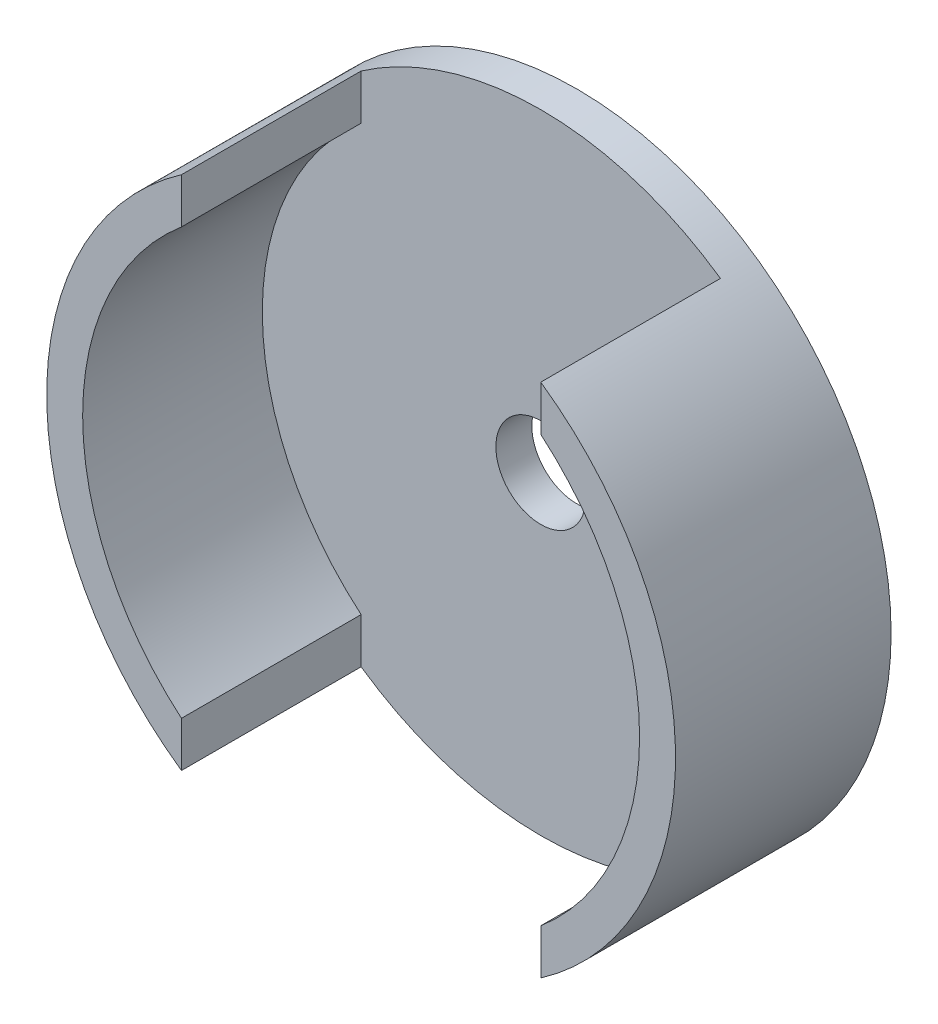
SolidWorks part; units mm, degrees
material "1060 Alloy"
ref_plane "Front Plane" through (0, 0, 0) normal (0, 0, 1) x (1, 0, 0)
ref_plane "Top Plane" through (0, 0, 0) normal (0, 1, 0) x (1, 0, 0)
ref_plane "Right Plane" through (0, 0, 0) normal (1, 0, 0) x (0, 0, -1)
sketch "Sketch1" plane through (0, 0, 0) normal (0, 0, 1) x (1, 0, 0)
  circle A0 centre (0, 0) radius 17.5
  dimension "D1" = 35
extrude "Boss-Extrude1" add sketch "Sketch1" along normal blind 12
shell "Shell4" thickness 2
sketch "Sketch3" plane through (0, 0, 0) normal (0, 0, 1) x (1, 0, 0)
  circle A0 centre (0, 0) radius 2.5
extrude "Cut-Extrude1" cut sketch "Sketch3" along normal through all both and the other way through all
sketch "Sketch4" plane through (0, 0, 0) normal (0, 1, 0) x (1, 0, 0)
  line L0 (0, 10.3606) -> (0, -25.7956) construction
  line L1 (-10, -2) -> (-10, -26.9407)
  line L2 (10, -2) -> (10, -26.9407)
  line L3 (-10, -2) -> (10, -2)
  line L4 (-10, -26.9407) -> (10, -26.9407)
  line L5 (-17.5, -12) -> (17.5, -12) construction
  dimension "D1" = 20
  dimension "D2" = 10
  dimension "D3" = 2
  dimension "D4" = 14.9407
extrude "Cut-Extrude2" cut sketch "Sketch4" against normal through all both and the other way through all
